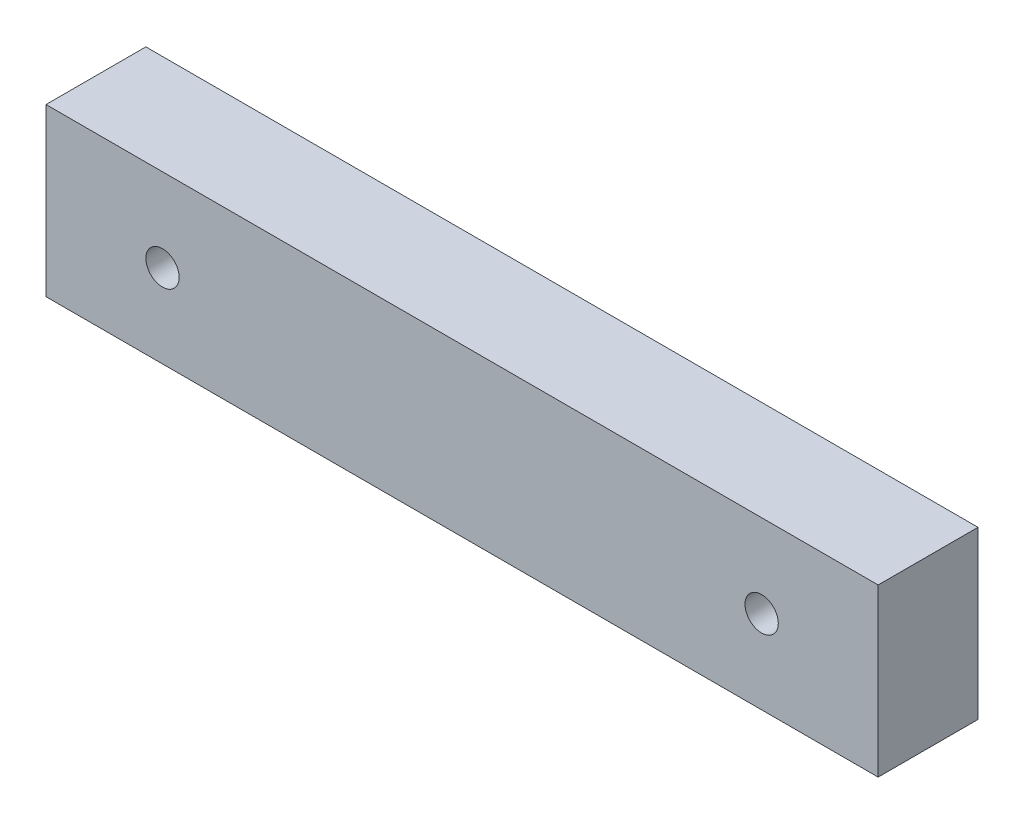
SolidWorks part; units mm, degrees
ref_plane "前视基准面" through (0, 0, 0) normal (0, 0, 1) x (1, 0, 0)
ref_plane "上视基准面" through (0, 0, 0) normal (0, 1, 0) x (1, 0, 0)
ref_plane "右视基准面" through (0, 0, 0) normal (1, 0, 0) x (0, 0, -1)
sketch "草图1" plane through (0, 0, 0) normal (0, 0, 1) x (1, 0, 0)
  line L1 (-62.5, 12.5) -> (62.5, 12.5)
  line L2 (-62.5, 12.5) -> (-62.5, -12.5)
  line L3 (-62.5, -12.5) -> (62.5, -12.5)
  line L4 (62.5, 12.5) -> (62.5, -12.5)
  line L5 (0, -12.5) -> (0, 12.5) construction
  line L6 (-62.5, 0) -> (62.5, 0) construction
  circle A0 centre (45, 0) radius 2.5
  circle A1 centre (-45, 0) radius 2.5
  point P0 (0, 0)
  dimension "D3" = 5
  dimension "D4" = 17.5
  dimension "D1" = 25
  dimension "D2" = 125
extrude "凸台-拉伸1" add sketch "草图1" along normal blind 15
